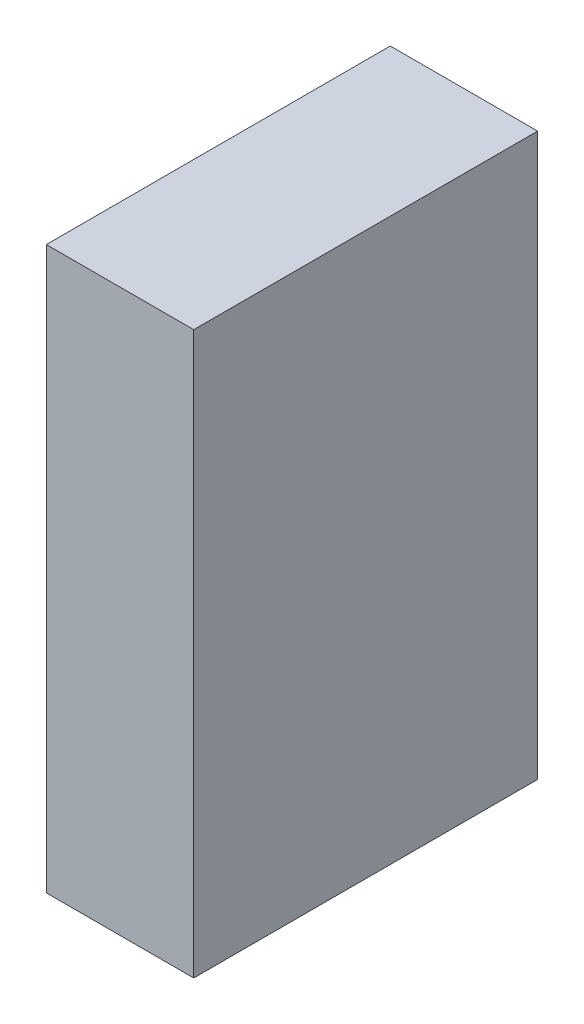
SolidWorks part; units mm, degrees
ref_plane "Płaszczyzna przednia" through (0, 0, 0) normal (0, 0, 1) x (1, 0, 0)
ref_plane "Płaszczyzna górna" through (0, 0, 0) normal (0, 1, 0) x (1, 0, 0)
ref_plane "Płaszczyzna prawa" through (0, 0, 0) normal (1, 0, 0) x (0, 0, -1)
sketch "Szkic1" plane through (0, 0, 0) normal (1, 0, 0) x (0, 0, -1)
  line L1 (0, 0) -> (98, 0)
  line L2 (0, 0) -> (0, 160)
  line L3 (0, 160) -> (98, 160)
  line L4 (98, 0) -> (98, 160)
  dimension "D1" = 98
  dimension "D2" = 160
extrude "Dodanie-wyciągnięcie1" add sketch "Szkic1" along normal blind 42
